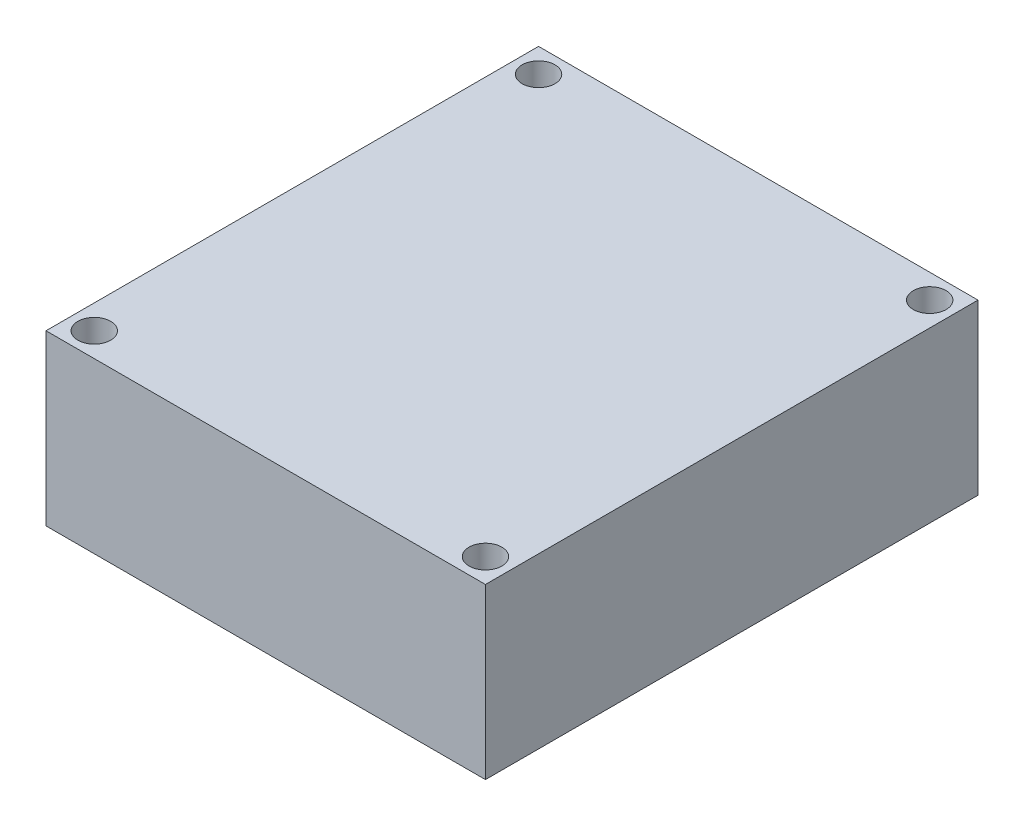
SolidWorks part; units mm, degrees
ref_plane "前视基准面" through (0, 0, 0) normal (0, 0, 1) x (1, 0, 0)
ref_plane "上视基准面" through (0, 0, 0) normal (0, 1, 0) x (1, 0, 0)
ref_plane "右视基准面" through (0, 0, 0) normal (1, 0, 0) x (0, 0, -1)
sketch "草图1" plane through (0, 0, 0) normal (0, 1, 0) x (1, 0, 0)
  line L1 (22.75, -25.5) -> (-22.75, -25.5)
  line L2 (22.75, -25.5) -> (22.75, 25.5)
  line L3 (22.75, 25.5) -> (-22.75, 25.5)
  line L4 (-22.75, -25.5) -> (-22.75, 25.5)
  line L5 (0, 25.5) -> (0, -25.5) construction
  line L6 (22.75, 0) -> (-22.75, 0) construction
  point P0 (0, 0)
  dimension "D1" = 51
  dimension "D2" = 45.5
extrude "凸台-拉伸1" add sketch "草图1" along normal blind 17.5
sketch "草图2" plane through (0, 17.5, 0) normal (0, 1, 0) x (1, 0, 0)
  line L0 (22.75, -25.5) -> (22.75, 25.5) construction
  line L1 (-22.75, -25.5) -> (22.75, -25.5) construction
  line L2 (-24.7707, 0) -> (25.4919, 0) construction
  line L3 (0, 28.1218) -> (0, -27.7801) construction
  circle A0 centre (20.25, -23) radius 1.7
  circle A1 centre (-20.25, -23) radius 1.7
  circle A2 centre (20.25, 23) radius 1.7
  circle A3 centre (-20.25, 23) radius 1.7
  dimension "D1" = 3.4
  dimension "D2" = 2.5
  dimension "D3" = 2.5
extrude "切除-拉伸1" cut sketch "草图2" against normal through all
